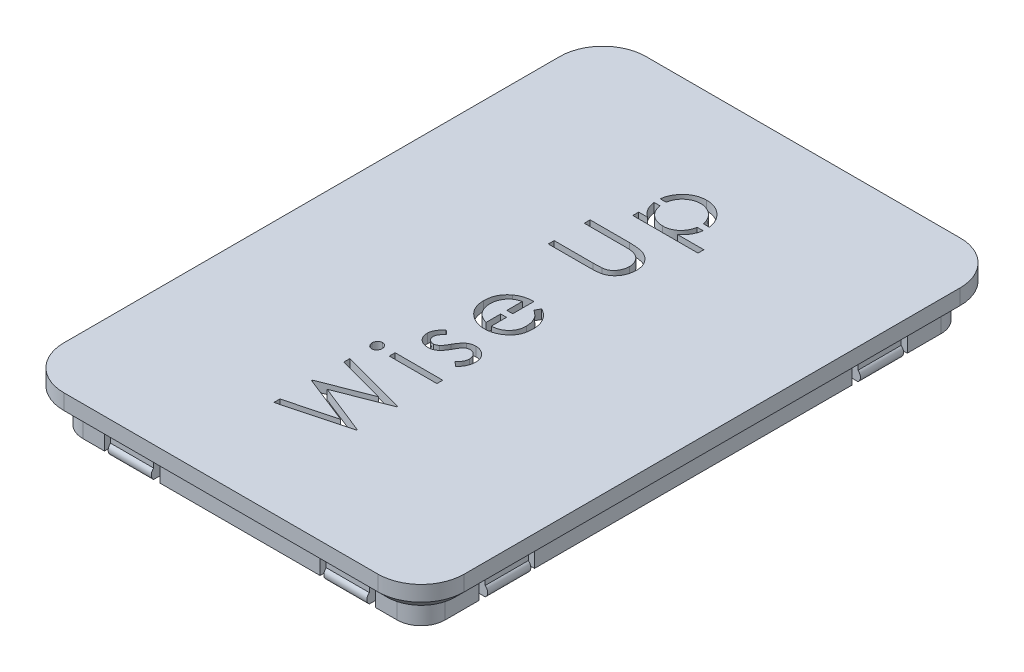
SolidWorks part; units mm, degrees
ref_plane "Front Plane" through (0, 0, 0) normal (0, 0, 1) x (1, 0, 0)
ref_plane "Top Plane" through (0, 0, 0) normal (0, 1, 0) x (1, 0, 0)
ref_plane "Right Plane" through (0, 0, 0) normal (1, 0, 0) x (0, 0, -1)
sketch "Sketch1" plane through (0, 0, 0) normal (0, 1, 0) x (1, 0, 0)
  line L4 (-30.5, 40) -> (-30.5, -40.5)
  line L5 (27.5, 47) -> (-23.5, 47)
  line L6 (34.5, -40.5) -> (34.5, 40)
  line L7 (-23.5, -47.5) -> (27.5, -47.5)
  line L8 (-30.5, 40) -> (-30.5, -40.5)
  line L9 (27.5, 47) -> (-23.5, 47)
  line L10 (34.5, -40.5) -> (34.5, 40)
  line L11 (-23.5, -47.5) -> (27.5, -47.5)
  arc A4 (-30.5, -40.5) -> (-23.5, -47.5) centre (-23.5, -40.5) ccw
  arc A5 (-23.5, 47) -> (-30.5, 40) centre (-23.5, 40) ccw
  arc A6 (34.5, 40) -> (27.5, 47) centre (27.5, 40) ccw
  arc A7 (27.5, -47.5) -> (34.5, -40.5) centre (27.5, -40.5) ccw
  arc A8 (-30.5, -40.5) -> (-23.5, -47.5) centre (-23.5, -40.5) ccw
  arc A9 (-23.5, 47) -> (-30.5, 40) centre (-23.5, 40) ccw
  arc A10 (34.5, 40) -> (27.5, 47) centre (27.5, 40) ccw
  arc A11 (27.5, -47.5) -> (34.5, -40.5) centre (27.5, -40.5) ccw
  dimension "D1" = 0
extrude "Boss-Extrude1" add sketch "Sketch1" along normal blind 4
chamfer "Chamfer1" distance 1.5 angle 45 8 edges at (-30.5, 0, 0.25) (-28.4497, 0, 45.4497) (-28.4497, 0, -44.9497) (2, 0, 47.5) (2, 0, -47) (32.4497, 0, 45.4497) (32.4497, 0, -44.9497) (34.5, 0, 0.25)
sketch "Sketch2" plane through (0, 0, 0) normal (0, -1, 0) x (1, 0, 0)
  line L4 (27.5, 43.4) -> (-23.5, 43.4)
  line L5 (-26.4, 40.5) -> (-26.4, -40)
  line L6 (-23.5, -42.9) -> (27.5, -42.9)
  line L7 (30.4, -40) -> (30.4, 40.5)
  line L8 (-27.4, 40.5) -> (-27.4, -40)
  line L9 (-23.5, -43.9) -> (27.5, -43.9)
  line L10 (31.4, -40) -> (31.4, 40.5)
  line L11 (27.5, 44.4) -> (-23.5, 44.4)
  line L12 (-27.4, 40.5) -> (-27.4, -40)
  line L13 (-23.5, -43.9) -> (27.5, -43.9)
  line L14 (31.4, -40) -> (31.4, 40.5)
  line L15 (27.5, 44.4) -> (-23.5, 44.4)
  arc A4 (-23.5, 43.4) -> (-26.4, 40.5) centre (-23.5, 40.5) ccw
  arc A5 (-26.4, -40) -> (-23.5, -42.9) centre (-23.5, -40) ccw
  arc A6 (27.5, -42.9) -> (30.4, -40) centre (27.5, -40) ccw
  arc A7 (30.4, 40.5) -> (27.5, 43.4) centre (27.5, 40.5) ccw
  arc A8 (-23.5, 44.4) -> (-27.4, 40.5) centre (-23.5, 40.5) ccw
  arc A9 (-27.4, -40) -> (-23.5, -43.9) centre (-23.5, -40) ccw
  arc A10 (27.5, -43.9) -> (31.4, -40) centre (27.5, -40) ccw
  arc A11 (31.4, 40.5) -> (27.5, 44.4) centre (27.5, 40.5) ccw
  arc A12 (-23.5, 44.4) -> (-27.4, 40.5) centre (-23.5, 40.5) ccw
  arc A13 (-27.4, -40) -> (-23.5, -43.9) centre (-23.5, -40) ccw
  arc A14 (27.5, -43.9) -> (31.4, -40) centre (27.5, -40) ccw
  arc A15 (31.4, 40.5) -> (27.5, 44.4) centre (27.5, 40.5) ccw
  dimension "D1" = 1.6
  dimension "D2" = 1
extrude "Boss-Extrude2" add sketch "Sketch2" along normal blind 4
sketch "Sketch3" plane through (0, 0, 0) normal (0, -1, 0) x (1, 0, 0)
  line L4 (30.4, -40) -> (30.4, 40.5)
  line L5 (27.5, 43.4) -> (-23.5, 43.4)
  line L6 (-26.4, 40.5) -> (-26.4, -40)
  line L7 (-23.5, -42.9) -> (27.5, -42.9)
  line L8 (30.4, -40) -> (30.4, 40.5)
  line L9 (27.5, 43.4) -> (-23.5, 43.4)
  line L10 (-26.4, 40.5) -> (-26.4, -40)
  line L11 (-23.5, -42.9) -> (27.5, -42.9)
  arc A4 (30.4, 40.5) -> (27.5, 43.4) centre (27.5, 40.5) ccw
  arc A5 (-23.5, 43.4) -> (-26.4, 40.5) centre (-23.5, 40.5) ccw
  arc A6 (-26.4, -40) -> (-23.5, -42.9) centre (-23.5, -40) ccw
  arc A7 (27.5, -42.9) -> (30.4, -40) centre (27.5, -40) ccw
  arc A8 (30.4, 40.5) -> (27.5, 43.4) centre (27.5, 40.5) ccw
  arc A9 (-23.5, 43.4) -> (-26.4, 40.5) centre (-23.5, 40.5) ccw
  arc A10 (-26.4, -40) -> (-23.5, -42.9) centre (-23.5, -40) ccw
  arc A11 (27.5, -42.9) -> (30.4, -40) centre (27.5, -40) ccw
  dimension "D1" = 0
extrude "Cut-Extrude1" cut sketch "Sketch3" against normal offset from surface (2.5 mm away) 1.5 up to face at (2, 4, 0.25)
sketch "Sketch4" plane through (0, 0, 0) normal (0, -1, 0) x (1, 0, 0)
  line L0 (27.5, 44.4) -> (-23.5, 44.4) construction
  line L1 (-20, 44.4) -> (-19, 44.4)
  line L2 (-20, 44.4) -> (-20, 43.4)
  line L3 (-20, 43.4) -> (-19, 43.4)
  line L4 (-19, 44.4) -> (-19, 43.4)
  line L5 (27.5, 43.4) -> (-23.5, 43.4) construction
  line L12 (-12, 44.4) -> (-11, 44.4)
  line L13 (-12, 44.4) -> (-12, 43.4)
  line L14 (-11, 44.4) -> (-11, 43.4)
  line L15 (-12, 43.4) -> (-11, 43.4)
  line L16 (27.5, 44.4) -> (-23.5, 44.4) construction
  dimension "D1" = 1
  dimension "D2" = 20
  dimension "D4" = 8
  dimension "D3" = 2
extrude "Cut-Extrude2" cut sketch "Sketch4" along normal up to surface (4 mm away) up to face at (2, -4, 0.25)
sketch "Sketch5" plane through (0, 0, 0) normal (0, -1, 0) x (1, 0, 0)
  line L0 (-27.4, 40.5) -> (-27.4, -40) construction
  line L1 (-27.4, 34) -> (-26.4, 34)
  line L2 (-27.4, 34) -> (-27.4, 35)
  line L3 (-27.4, 35) -> (-26.4, 35)
  line L4 (-26.4, 34) -> (-26.4, 35)
  line L5 (-26.4, 40.5) -> (-26.4, -40) construction
  line L7 (-27.4, 27) -> (-26.4, 27)
  line L8 (-27.4, 27) -> (-27.4, 26)
  line L9 (-27.4, 26) -> (-26.4, 26)
  line L10 (-26.4, 27) -> (-26.4, 26)
  dimension "D1" = 1
  dimension "D2" = 35
  dimension "D3" = 8
  dimension "D4" = 1
extrude "Cut-Extrude3" cut sketch "Sketch5" along normal up to surface (4 mm away) up to face at (-1.5, -4, 8.98)
sketch "Sketch6" plane through (0, 0, 27) normal (0, 0, -1) x (-1, 0, 0)
  line L0 (27.4, -4) -> (27.4, 0) construction
  line L1 (27.4, -4) -> (27.4, -2.4)
  arc A0 (27.4, -4) -> (27.4, -2.4) centre (26.8, -3.2) ccw
  point P3 (27.8, -3.2)
  dimension "D1" = 1
  dimension "D2" = 0.4
extrude "Boss-Extrude3" add sketch "Sketch6" against normal up to surface (7 mm away) contours A0 L1 up to face at (-26.9, -2, 34)
sketch "Sketch7" plane through (-19, 0, 0) normal (-1, 0, 0) x (0, 0, 1)
  line L0 (44.4, -4) -> (44.4, 0) construction
  line L1 (44.4, -2.4) -> (44.4, -4)
  arc A0 (44.4, -4) -> (44.4, -2.4) centre (43.8, -3.2) ccw
  point P3 (44.8, -3.2)
  dimension "D2" = 1
  dimension "D1" = 0.4
extrude "Boss-Extrude4" add sketch "Sketch7" against normal up to surface (7 mm away) up to face at (-12, -2, 43.9)
ref_plane "Plane1" through (0, 0, 0.25) normal (0, 0, -1) x (-1, 0, 0)
ref_plane "Plane2" through (2, 0, 0) normal (1, 0, 0) x (0, 0, -1)
mirror "Mirror1" about plane through (2, 0, 0) normal (1, 0, 0) of "Boss-Extrude4", "Boss-Extrude3", "Cut-Extrude3", "Cut-Extrude2"
mirror "Mirror2" about plane through (0, 0, 0.25) normal (0, 0, -1) of "Mirror1", "Cut-Extrude2", "Cut-Extrude3", "Boss-Extrude3", "Boss-Extrude4"
sketch "Sketch9" plane through (0, 4, 0) normal (0, 1, 0) x (1, 0, 0)
  line L0 (5.5, -32.5) -> (5.5, 32) construction
  line L1 (-23.5, -47.5) -> (27.5, -47.5) construction
  line L2 (27.5, 47) -> (-23.5, 47) construction
  line L3 (-30.5, 40) -> (-30.5, -40.5) construction
  text T0 "Wise Up" font "Century Gothic" height in points 40
  dimension "D1" = 15
  dimension "D2" = 15
  dimension "D3" = 36
extrude "Cut-Extrude4" cut sketch "Sketch9" against normal up to surface (1.5 mm away) up to face at (2, 2.5, 0.25)
ref_plane "Plane3" through (0, 4, 0) normal (0, 1, 0) x (1, 0, 0)
sketch "Sketch11" plane through (0, 4, 0) normal (0, 1, 0) x (1, 0, 0)
  line L1 (6.6224, 27.1539) -> (-3.3776, 27.1539)
  line L2 (6.6224, 27.1539) -> (6.6224, 28.1539)
  line L3 (6.6224, 28.1539) -> (-3.3776, 28.1539)
  line L4 (-3.3776, 27.1539) -> (-3.3776, 28.1539)
  line L5 (6.6224, 27.1539) -> (-3.3776, 28.1539) construction
  line L6 (6.6224, 28.1539) -> (-3.3776, 27.1539) construction
  line L8 (-0.8, -0.9747) -> (4.2, -0.9747)
  line L9 (-0.8, -0.9747) -> (-0.8, 0.0253)
  line L10 (-0.8, 0.0253) -> (4.2, 0.0253)
  line L11 (4.2, -0.9747) -> (4.2, 0.0253)
  line L12 (-0.8, -0.9747) -> (4.2, 0.0253) construction
  line L13 (-0.8, 0.0253) -> (4.2, -0.9747) construction
  point P2 (1.6224, 27.6539)
  point P7 (1.7, -0.4747)
  dimension "D1" = 27.6539
  dimension "D2" = 1.6224
  dimension "D3" = 1
  dimension "D4" = 10
  dimension "D5" = 0.4747
  dimension "D6" = 1
  dimension "D7" = 5
  dimension "D8" = 1.7
extrude "Boss-Extrude6" add sketch "Sketch11" against normal blind 1.5
